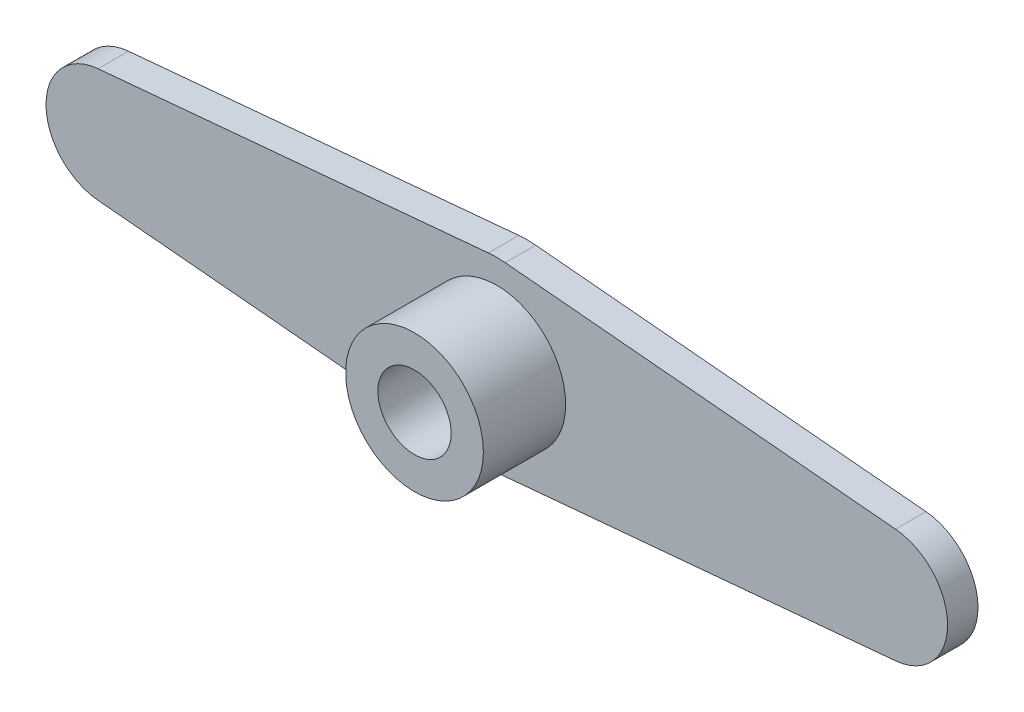
SolidWorks part; units mm, degrees
ref_plane "Front Plane" through (0, 0, 0) normal (0, 0, 1) x (1, 0, 0)
ref_plane "Top Plane" through (0, 0, 0) normal (0, 1, 0) x (1, 0, 0)
ref_plane "Right Plane" through (0, 0, 0) normal (1, 0, 0) x (0, 0, -1)
sketch "Sketch1" plane through (0, 0, 0) normal (0, 0, 1) x (1, 0, 0)
  line L0 (-27.94, 0) -> (27.94, 0) construction
  line L1 (-28.3095, 4.0472) -> (-0.6004, 6.5767)
  line L2 (0.6004, 6.5767) -> (28.3095, 4.0472)
  line L3 (28.3095, -4.0472) -> (0.6004, -6.5767)
  line L4 (-28.3095, -4.0472) -> (-0.6004, -6.5767)
  arc A0 (-0.6004, -6.5767) -> (0.6004, -6.5767) centre (0, 0) ccw
  arc A1 (-28.3095, 4.0472) -> (-28.3095, -4.0472) centre (-27.94, 0) ccw
  arc A2 (28.3095, -4.0472) -> (28.3095, 4.0472) centre (27.94, 0) ccw
  arc A3 (0.6004, 6.5767) -> (-0.6004, 6.5767) centre (0, 0) ccw
  point P15 (-37.7465, 0)
  dimension "D1" = 8.128
  dimension "D2" = 13.208
  dimension "D3" = 55.88
extrude "Boss-Extrude1" add sketch "Sketch1" along normal blind 2.159 contours L1 A3 L2 A2 L3 A0 L4 A1
sketch "Sketch2" plane through (0, 0, 2.159) normal (0, 0, 1) x (1, 0, 0)
  circle A0 centre (0, 0) radius 4.8895
  circle A1 centre (0, 0) radius 2.6035
  dimension "D1" = 9.779
  dimension "D2" = 2.286
extrude "Boss-Extrude2" add sketch "Sketch2" along normal blind 5.842
